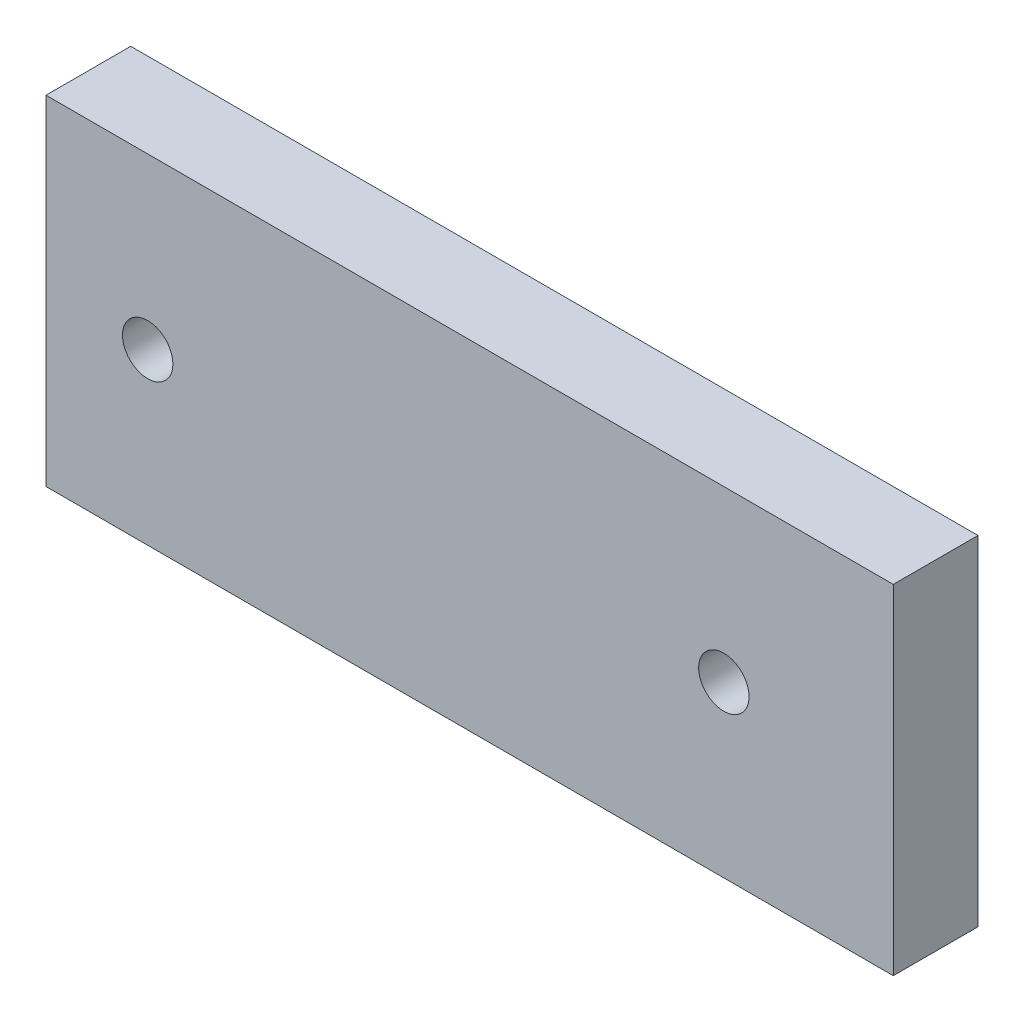
SolidWorks part; units mm, degrees
ref_plane "Front Plane" through (0, 0, 0) normal (0, 0, 1) x (1, 0, 0)
ref_plane "Top Plane" through (0, 0, 0) normal (0, 1, 0) x (1, 0, 0)
ref_plane "Right Plane" through (0, 0, 0) normal (1, 0, 0) x (0, 0, -1)
sketch "Sketch1" plane through (0, 0, 0) normal (0, 0, 1) x (1, 0, 0)
  line L1 (-25, 10) -> (25, 10)
  line L2 (-25, 10) -> (-25, -10)
  line L3 (-25, -10) -> (25, -10)
  line L4 (25, 10) -> (25, -10)
  circle A0 centre (-19, 0) radius 1.4857
  circle A1 centre (15, 0) radius 1.4857
  point P4 (-25, 0)
  point P7 (0, 10)
  dimension "D1" = 20
  dimension "D2" = 50
  dimension "D3" = 19
  dimension "D4" = 15
extrude "Boss-Extrude1" add sketch "Sketch1" against normal blind 5
